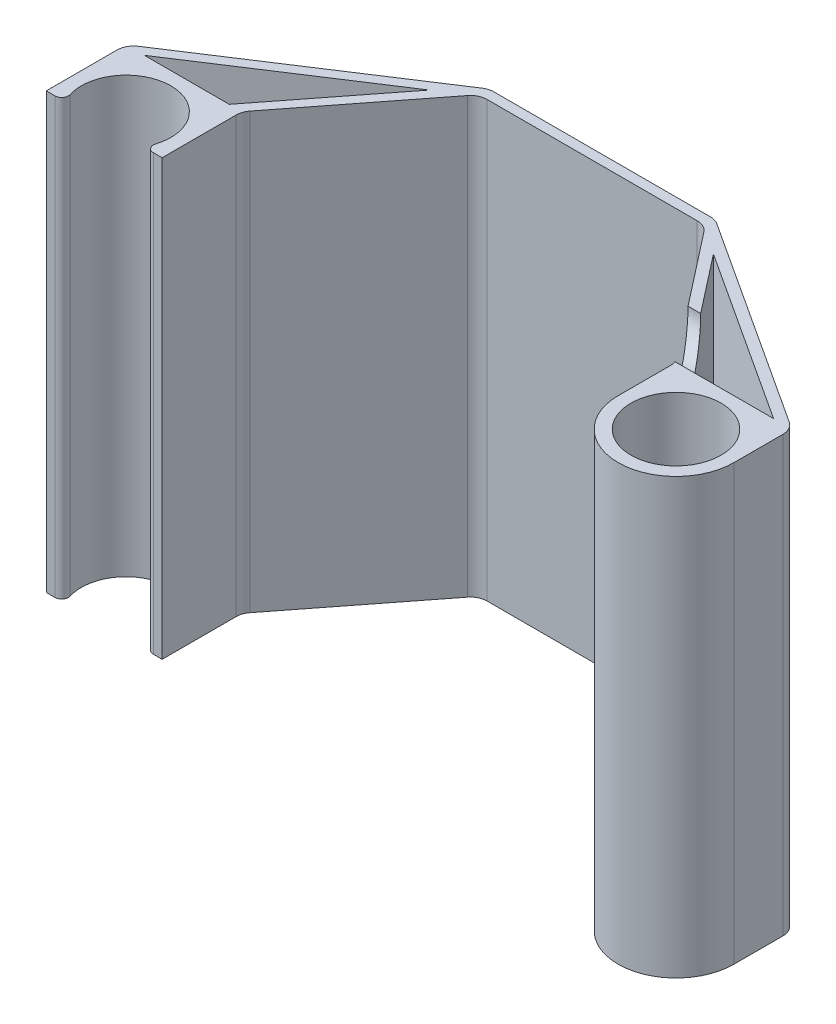
SolidWorks part; units mm, degrees
ref_plane "Front Plane" through (0, 0, 0) normal (0, 0, 1) x (1, 0, 0)
ref_plane "Top Plane" through (0, 0, 0) normal (0, 1, 0) x (1, 0, 0)
ref_plane "Right Plane" through (0, 0, 0) normal (1, 0, 0) x (0, 0, -1)
sketch "Sketch1" plane through (0, 0, 0) normal (0, 1, 0) x (1, 0, 0)
  line L0 (0, 0) -> (-34, 0)
  line L1 (-34, 0) -> (-100, -43)
  line L2 (-100, -43) -> (-100, -66.97)
  line L3 (-100, -66.97) -> (-97.3586, -66.97)
  line L4 (-67.8414, -66.97) -> (-65.2, -66.97)
  line L5 (-65.2, -66.97) -> (-65.2, -43)
  line L6 (-69.0047, -43) -> (-94.5043, -43)
  line L7 (-94.5043, -43) -> (-42.6567, -9.2205)
  line L8 (-34, -3) -> (0, -3)
  line L9 (0, -3) -> (0, 0)
  line L10 (-69.0047, -43) -> (-42.6567, -9.2205)
  line L11 (-34, -3) -> (-65.2, -43)
  arc A0 (-95.4481, -64.3784) -> (-69.7519, -64.3784) centre (-82.6, -60.4) cw
  arc A1 (-67.8414, -66.97) -> (-69.7519, -64.3784) centre (-67.8414, -64.97) cw
  arc A2 (-95.4481, -64.3784) -> (-97.3586, -66.97) centre (-97.3586, -64.97) cw
  dimension "D3" = 13.45
  dimension "D11" = 2
  dimension "D1" = 100
  dimension "D2" = 34.8
  dimension "D4" = 17.4
  dimension "D5" = 23.97
  dimension "D6" = 3
  dimension "D7" = 43
  dimension "D8" = 3
  dimension "D9" = 3
  dimension "D10" = 3
  dimension "D12" = 66
extrude "Boss-Extrude1" add sketch "Sketch1" along normal blind 130.5 contours L5 L11 L8 L9 L0 L1 L2 L3 A2 A0 A1 L4
mirror "Mirror1" about plane through (0, 130.5, 3) normal (-1, 0, 0) of "Boss-Extrude1"
sketch "Sketch4" plane through (0, 0, 0) normal (0, -1, 0) x (1, 0, 0)
  line L5 (100, 43) -> (100, 66.97) construction
  line L6 (65.2, 43) -> (100, 43)
  line L7 (65.2, 43) -> (65.2, 77.8)
  line L8 (65.2, 77.8) -> (100, 77.8)
  line L9 (100, 43) -> (100, 77.8)
  circle A0 centre (82.6, 60.4) radius 13.45
  arc A1 (69.7519, 64.3784) -> (95.4481, 64.3784) centre (82.6, 60.4) ccw construction
extrude "Boss-Extrude2" add sketch "Sketch4" against normal up to vertex (130.5 mm away)
fillet "Fillet1" radius 5 8 edges at (-100, 65.25, 43) (-34, 65.25, 0) (34, 65.25, 0) (100, 65.25, 43) (65.2, 65.25, 43) (34, 65.25, 3) (-34, 65.25, 3) (-65.2, 65.25, 43)
sketch "Sketch5" plane through (0, 0, 0) normal (0, -1, 0) x (1, 0, 0)
  line L0 (65.2, 77.8) -> (65.2, 44.7194) construction
  line L1 (65.2, 60.4) -> (65.2, 77.8)
  line L3 (100, 77.8) -> (100, 60.4)
  line L4 (65.2, 77.8) -> (83.0702, 82.4044)
  line L5 (83.0702, 82.4044) -> (100, 77.8)
  arc A0 (100, 60.4) -> (65.2, 60.4) centre (82.6, 60.4) ccw
extrude "Cut-Extrude4" cut sketch "Sketch5" against normal through all
sketch "Sketch7" plane through (65.2, 0, 0) normal (-1, 0, 0) x (0, 0, 1)
  circle A0 centre (34.8, 0) radius 8.2
  circle A1 centre (34.8, 130.5) radius 8.2
  dimension "D1" = 16.4
extrude "Cut-Extrude5" cut sketch "Sketch7" against normal up to next and the other way up to next
sketch "Sketch8" plane through (0, 0, 0) normal (0, -1, 0) x (1, 0, 0)
  circle A0 centre (82.6, 60.4) radius 13.55
  dimension "D1" = 27.1
extrude "Cut-Extrude6" cut sketch "Sketch8" against normal through all
